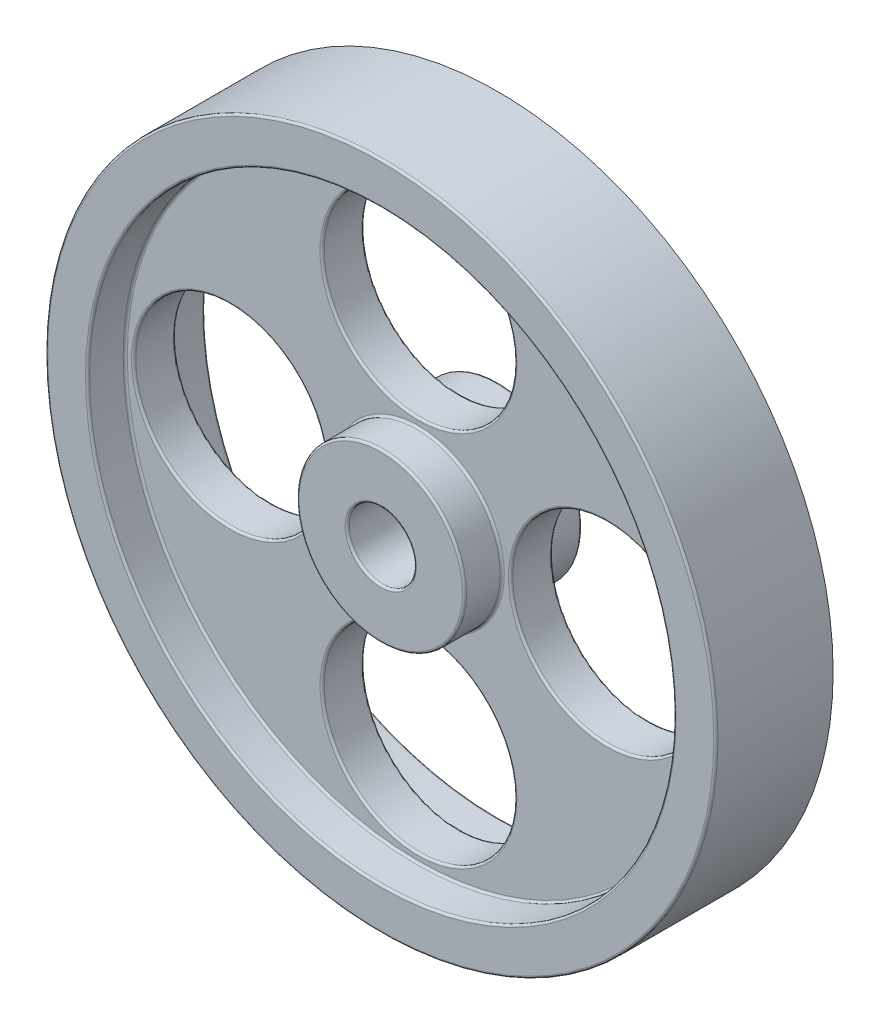
SolidWorks part; units mm, degrees
ref_plane "Front Plane" through (0, 0, 0) normal (0, 0, 1) x (1, 0, 0)
ref_plane "Top Plane" through (0, 0, 0) normal (0, 1, 0) x (1, 0, 0)
ref_plane "Right Plane" through (0, 0, 0) normal (1, 0, 0) x (0, 0, -1)
sketch "Sketch1" plane through (0, 0, 0) normal (0, 0, 1) x (1, 0, 0)
  circle A0 centre (0, 0) radius 1016
  circle A1 centre (0, 0) radius 101.6
  dimension "D1" = 2032
  dimension "D2" = 203.2
extrude "Boss-Extrude1" add sketch "Sketch1" along normal mid plane 355.6
sketch "Sketch2" plane through (0, 0, 177.8) normal (0, 0, 1) x (1, 0, 0)
  circle A0 centre (0, 0) radius 101.6
  circle A1 centre (0, 0) radius 889
  dimension "D1" = 1778
extrude "Cut-Extrude1" cut sketch "Sketch2" against normal blind 114.3
sketch "Sketch3" plane through (0, 0, 63.5) normal (0, 0, 1) x (1, 0, 0)
  circle A0 centre (0, 0) radius 101.6
  circle A1 centre (0, 0) radius 254
  dimension "D1" = 508
extrude "Boss-Extrude2" add sketch "Sketch3" along normal blind 114.3
sketch "Sketch4" plane through (0, 0, 63.5) normal (0, 0, 1) x (1, 0, 0)
  circle A0 centre (0, 0) radius 571.5 construction
  circle A1 centre (0, 571.5) radius 292.1
  circle A2 centre (571.5, 0) radius 292.1
  circle A3 centre (0, -571.5) radius 292.1
  circle A4 centre (-571.5, 0) radius 292.1
  point P14 (0, 0)
  dimension "D1" = 1143
  dimension "D2" = 584.2
  dimension "D3" = 4
extrude "Cut-Extrude2" cut sketch "Sketch4" against normal through all both and the other way through all
mirror "Mirror1" about plane through (0, 0, 0) normal (0, 0, 1) of "Cut-Extrude1"
mirror "Mirror2" about plane through (0, 0, 0) normal (0, 0, 1) of "Boss-Extrude2"
fillet "Fillet1" radius 6.35 19 edges at (889, 0, -177.8) (-292.1, 571.5, -63.5) (-863.6, 0, -63.5) (279.4, 0, -63.5) (-292.1, -571.5, -63.5) (889, 0, -63.5) (-254, 0, -63.5) (254, 0, -177.8) (101.6, 0, -177.8) (101.6, 0, 177.8) (254, 0, 177.8) (1016, 0, 177.8) (889, 0, 177.8) (254, 0, 63.5) (889, 0, 63.5) (292.1, 571.5, 63.5) (-279.4, 0, 63.5) (863.6, 0, 63.5) (292.1, -571.5, 63.5)
